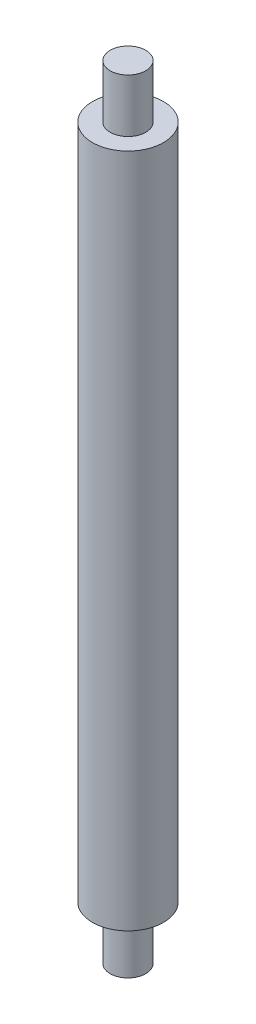
SolidWorks part; units mm, degrees
ref_plane "Plan de face" through (0, 0, 0) normal (0, 0, 1) x (1, 0, 0)
ref_plane "Plan de dessus" through (0, 0, 0) normal (0, 1, 0) x (1, 0, 0)
ref_plane "Plan de droite" through (0, 0, 0) normal (1, 0, 0) x (0, 0, -1)
sketch "Esquisse1" plane through (0, 0, 0) normal (0, 0, 1) x (1, 0, 0)
  line L0 (0, 0) -> (0, 11) construction
  line L1 (0, 11) -> (0.5, 11)
  line L2 (0.5, 11) -> (0.5, 9.5)
  line L3 (0.5, 9.5) -> (1, 9.5)
  line L4 (1, 9.5) -> (1, -9.5)
  line L5 (1, -9.5) -> (0.5, -9.5)
  line L6 (0.5, -9.5) -> (0.5, -11)
  line L7 (0.5, -11) -> (0, -11)
  line L8 (0, 0) -> (1, 0) construction
  line L9 (0, 11) -> (0, -11)
  point P3 (0, -11)
  dimension "D1" = 1
  dimension "D2" = 2
  dimension "D3" = 19
  dimension "D4" = 1.5
revolve "Révolution1" add sketch "Esquisse1" angle 360 about L9
